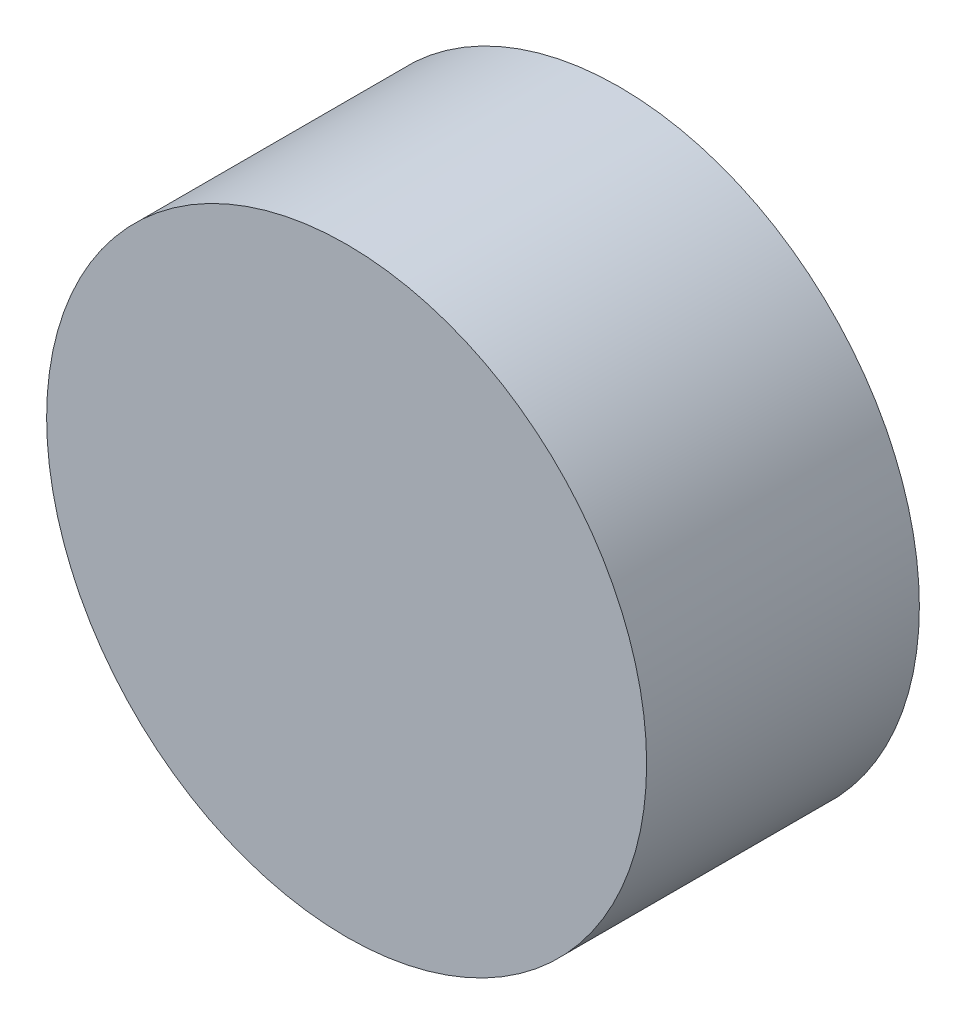
SolidWorks part; units mm, degrees
ref_plane "前视基准面" through (0, 0, 0) normal (0, 0, 1) x (1, 0, 0)
ref_plane "上视基准面" through (0, 0, 0) normal (0, 1, 0) x (1, 0, 0)
ref_plane "右视基准面" through (0, 0, 0) normal (1, 0, 0) x (0, 0, -1)
other "Configuration Table"
sketch "草图1" plane through (0, 0, 0) normal (0, 0, 1) x (1, 0, 0)
  circle A0 centre (0, 0) radius 22
extrude "凸台-拉伸1" add sketch "草图1" along normal blind 20
